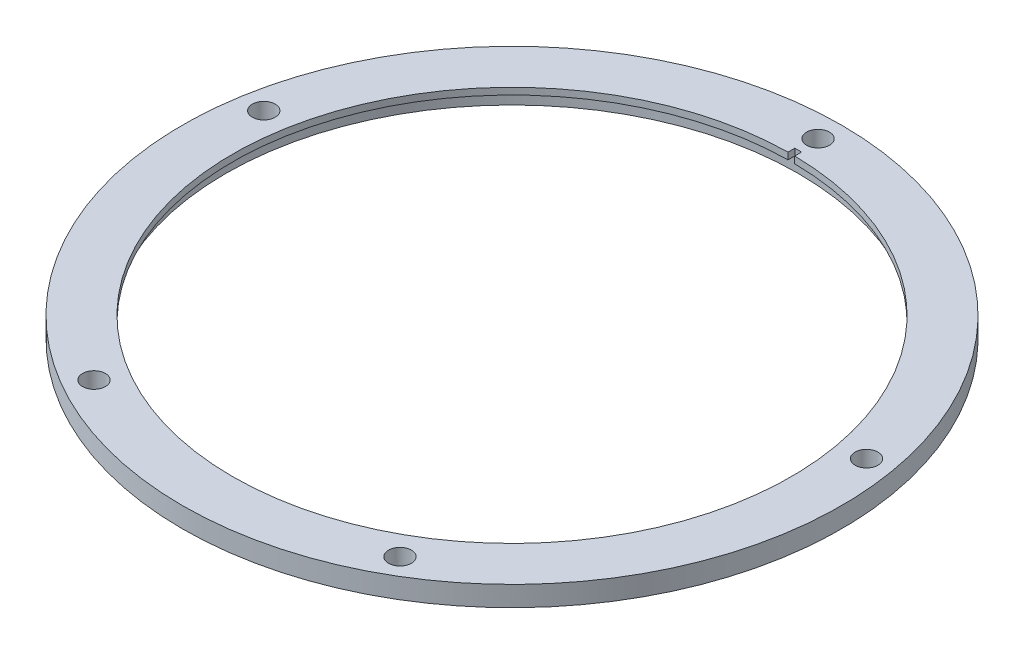
SolidWorks part; units mm, degrees
material "6061 Alloy"
ref_plane "Front Plane" through (0, 0, 0) normal (0, 0, 1) x (1, 0, 0)
ref_plane "Top Plane" through (0, 0, 0) normal (0, 1, 0) x (1, 0, 0)
ref_plane "Right Plane" through (0, 0, 0) normal (1, 0, 0) x (0, 0, -1)
sketch "Sketch1" plane through (0, 0, 0) normal (0, 1, 0) x (1, 0, 0)
  circle A0 centre (-17.2343, -2.9886) radius 41.538
  circle A1 centre (-17.2343, -2.9886) radius 49
extrude "Boss-Extrude1" add sketch "Sketch1" along normal blind 1
sketch "Sketch2" plane through (0, 1, 0) normal (0, 1, 0) x (1, 0, 0)
  line L3 (-16.7343, 38.5463) -> (-16.7343, 39.5464)
  line L4 (-17.7343, 38.5463) -> (-17.7343, 39.5464)
  arc A3 (-16.7343, 39.5464) -> (-17.7343, 39.5464) centre (-17.2343, -2.9886) ccw
  arc A4 (-16.7343, 38.5463) -> (-17.7343, 38.5463) centre (-17.2343, -2.9886) ccw
extrude "Cut-Extrude1" cut sketch "Sketch2" against normal blind 10
sketch "Sketch3" plane through (0, 0, 0) normal (0, -1, 0) x (1, 0, 0)
  line L0 (-17.7343, -38.5463) -> (-17.7343, -39.5584)
  line L1 (-16.7343, -38.5463) -> (-16.7343, -39.5584)
  arc A1 (-17.7343, -38.5463) -> (-16.7343, -38.5463) centre (-17.2343, 2.9886) ccw
  arc A2 (-17.7343, -39.5584) -> (-16.7343, -39.5584) centre (-17.2343, 2.9886) ccw
extrude "Cut-Extrude2" cut sketch "Sketch3" against normal blind 10
sketch "Sketch4" plane through (0, 0, 0) normal (0, -1, 0) x (1, 0, 0)
  circle A0 centre (-17.2343, 2.9886) radius 42.55
  circle A1 centre (-17.2343, 2.9886) radius 49
extrude "Boss-Extrude2" add sketch "Sketch4" along normal blind 2
extrude "Cut-Extrude3" cut sketch "Sketch5" against normal through all
sketch "Sketch5" plane through (12.1573, 4, 5.6) normal (0, 1, 0) x (1, 0, 0)
  line L0 (-29.3916, 2.6114) -> (-29.3916, 48.1114) construction
  line L1 (-29.3916, 2.6114) -> (-52.1416, -36.7928) construction
  line L2 (-29.3916, 2.6114) -> (-74.2003, 10.5124) construction
  line L3 (-29.3916, 2.6114) -> (-6.6416, -36.7928) construction
  line L4 (-29.3916, 2.6114) -> (15.4172, 10.5124) construction
  circle A0 centre (-29.3916, 48.1114) radius 1.7
  circle A1 centre (-74.2003, 10.5124) radius 1.7
  circle A2 centre (-52.1416, -36.7928) radius 1.7
  circle A3 centre (-6.6416, -36.7928) radius 1.7
  circle A4 centre (15.4172, 10.5124) radius 1.7
